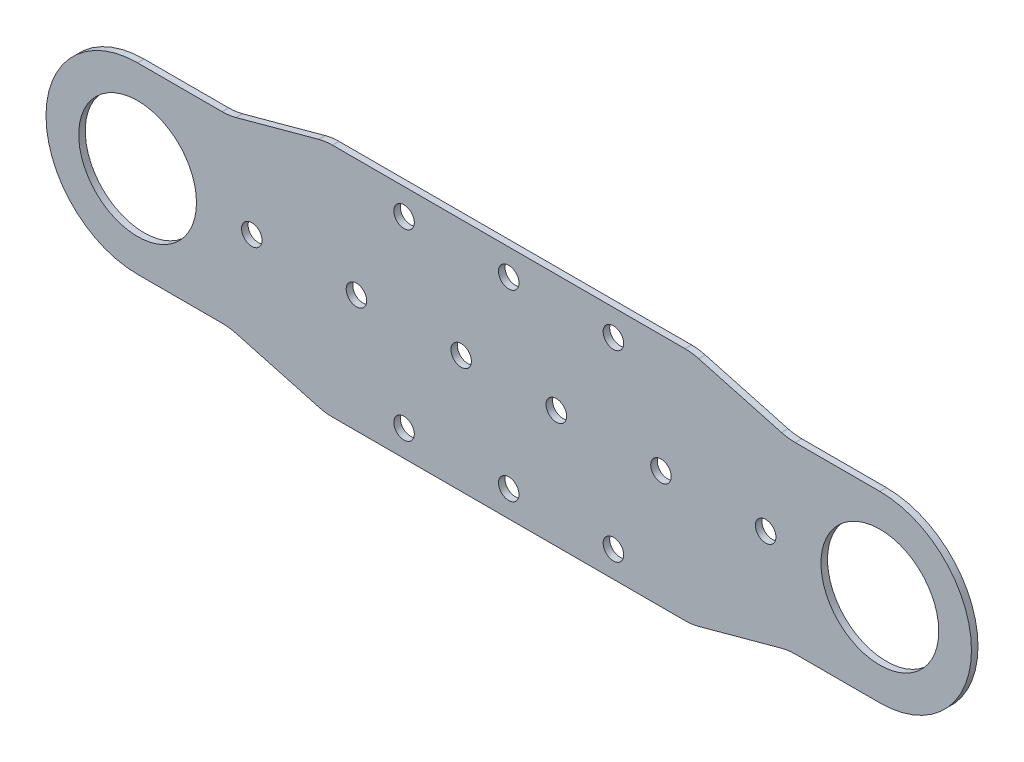
SolidWorks part; units mm, degrees
material "6061-T6 (SS)"
ref_plane "Front Plane" through (0, 0, 0) normal (0, 0, 1) x (1, 0, 0)
ref_plane "Top Plane" through (0, 0, 0) normal (0, 1, 0) x (1, 0, 0)
ref_plane "Right Plane" through (0, 0, 0) normal (1, 0, 0) x (0, 0, -1)
sketch "Sketch1" plane through (0, 0, 0) normal (0, 0, 1) x (1, 0, 0)
  line L0 (0, 0) -> (180.1114, 0) construction
  line L1 (0, 22.225) -> (22.225, 22.225)
  line L2 (22.225, 22.225) -> (45.6057, 28.575)
  line L3 (45.6057, 28.575) -> (134.5057, 28.575)
  line L4 (134.5057, 28.575) -> (157.8864, 22.225)
  line L5 (157.8864, 22.225) -> (180.1114, 22.225)
  line L6 (157.8864, -22.225) -> (180.1114, -22.225)
  line L7 (134.5057, -28.575) -> (157.8864, -22.225)
  line L8 (45.6057, -28.575) -> (134.5057, -28.575)
  line L9 (22.225, -22.225) -> (45.6057, -28.575)
  line L10 (0, -22.225) -> (22.225, -22.225)
  circle A0 centre (0, 0) radius 14.2875
  circle A1 centre (0, 0) radius 22.225 construction
  circle A2 centre (180.1114, 0) radius 14.2875
  circle A3 centre (180.1114, 0) radius 22.225 construction
  arc A4 (180.1114, 22.225) -> (180.1114, -22.225) centre (180.1114, 0) cw
  arc A5 (0, 22.225) -> (0, -22.225) centre (0, 0) ccw
  dimension "D1" = 28.575
  dimension "D2" = 44.45
  dimension "D3" = 180.1114
  dimension "D4" = 88.9
  dimension "D5" = 22.225
  dimension "D6" = 28.575
extrude "Boss-Extrude1" add sketch "Sketch1" along normal blind 1.5875
hole_wizard "#10 Clearance Hole1" positions "Sketch2" profile "Sketch3" hole size "#10" standard "ANSI Inch" end condition through all
sketch "Sketch2" plane through (0, 0, 1.5875) normal (0, 0, 1) x (1, 0, 0)
  line L0 (90.0557, -28.575) -> (90.0557, 28.575) construction
  line L1 (45.6057, -28.575) -> (134.5057, -28.575) construction
  line L2 (134.5057, 28.575) -> (45.6057, 28.575) construction
  line L4 (0, 0) -> (180.1114, 0) construction
  line L5 (90.0557, 22.225) -> (64.6557, 22.225) construction
  line L7 (27.7114, 0) -> (53.1114, 0) construction
  point P15 (27.7114, 0)
  point P17 (64.6557, 22.225)
  point P19 (90.0557, 22.225)
  point P33 (53.1114, 0)
  point P34 (78.5114, 0)
  point P37 (101.6, 0)
  point P38 (127, 0)
  point P39 (115.4557, 22.225)
  point P40 (152.4, 0)
  point P41 (115.4557, -22.225)
  point P42 (90.0557, -22.225)
  point P43 (64.6557, -22.225)
  dimension "D1" = 25.4
  dimension "D2" = 22.225
  dimension "D3" = 27.7114
  dimension "D5" = 25.4
  dimension "D4" = 3
sketch "Sketch3" plane through (64.6557, -22.225, 1.5875) normal (1, 0, 0) x (0, -1, 0)
  line L0 (0, 0) -> (0, 1.5875)
  line L1 (0, 1.5875) -> (2.4892, 1.5875)
  line L2 (2.4892, 1.5875) -> (2.4892, 0)
  line L5 (2.4892, 0) -> (0, 0)
  line L11 (0, -6.35) -> (0, 107.95) construction
  dimension "Thru Hole Dia." = 4.9784
  dimension "Thru Hole Depth" = 1.5875
fillet "Fillet1" radius 12.7 8 edges at (22.225, 22.225, 0.7937) (134.5057, 28.575, 0.7937) (157.8864, 22.225, 0.7937) (157.8864, -22.225, 0.7937) (134.5057, -28.575, 0.7937) (45.6057, -28.575, 0.7937) (22.225, -22.225, 0.7937) (45.6057, 28.575, 0.7937)
